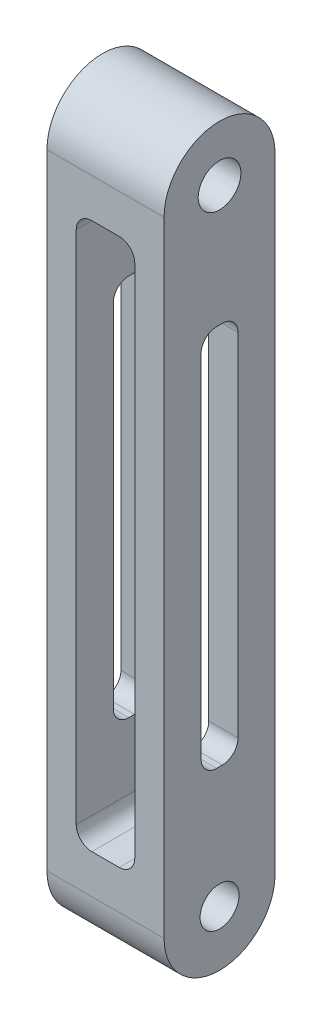
SolidWorks part; units mm, degrees
ref_plane "Front Plane" through (0, 0, 0) normal (0, 0, 1) x (1, 0, 0)
ref_plane "Top Plane" through (0, 0, 0) normal (0, 1, 0) x (1, 0, 0)
ref_plane "Right Plane" through (0, 0, 0) normal (1, 0, 0) x (0, 0, -1)
sketch "Sketch2" plane through (0, 0, 0) normal (1, 0, 0) x (0, 0, -1)
  line L0 (-7.1086, 0) -> (-7.1086, -80)
  line L1 (7.1086, 0) -> (7.1086, -80)
  line L2 (-7.1086, 0) -> (7.1086, 0)
  line L3 (7.1086, -80) -> (-7.1086, -80)
  line L4 (0, 0) -> (0, -40)
  line L6 (-0.3662, -15.5) -> (0.3662, -15.5)
  line L7 (-2.3662, -17.5) -> (-2.3662, -62.5)
  line L8 (-0.3662, -64.5) -> (0.3662, -64.5)
  line L9 (2.3662, -17.5) -> (2.3662, -62.5)
  line L10 (-2.3662, -15.5) -> (2.3662, -64.5) construction
  line L11 (-2.3662, -64.5) -> (2.3662, -15.5) construction
  circle A0 centre (0, 0) radius 2.7341
  circle A1 centre (0, 0) radius 7.1086
  circle A2 centre (0, -80) radius 7.1086
  circle A3 centre (0, -80) radius 2.5
  arc A4 (0.3662, -64.5) -> (2.3662, -62.5) centre (0.3662, -62.5) ccw
  arc A5 (-0.3662, -64.5) -> (-2.3662, -62.5) centre (-0.3662, -62.5) cw
  arc A6 (0.3662, -15.5) -> (2.3662, -17.5) centre (0.3662, -17.5) cw
  arc A7 (-2.3662, -17.5) -> (-0.3662, -15.5) centre (-0.3662, -17.5) cw
  dimension "D1" = 80
  dimension "D2" = 40
  dimension "D3" = 2
  dimension "D4" = 45
extrude "Boss-Extrude1" add sketch "Sketch2" along normal blind 15
sketch "Sketch3" plane through (0, 0, -7.1086) normal (0, 0, -1) x (-1, 0, 0)
  line L0 (-7.5, 0) -> (-7.5, -80)
  line L1 (-15, 0) -> (0, 0) construction
  line L2 (-15, -80) -> (0, -80) construction
  line L4 (-9.25, -5) -> (-5.75, -5)
  line L5 (-11.25, -7) -> (-11.25, -73)
  line L6 (-9.25, -75) -> (-5.75, -75)
  line L7 (-3.75, -7) -> (-3.75, -73)
  line L8 (-11.25, -5) -> (-3.75, -75) construction
  line L9 (-11.25, -75) -> (-3.75, -5) construction
  arc A0 (-11.25, -73) -> (-9.25, -75) centre (-9.25, -73) ccw
  arc A1 (-3.75, -73) -> (-5.75, -75) centre (-5.75, -73) cw
  arc A2 (-3.75, -7) -> (-5.75, -5) centre (-5.75, -7) ccw
  arc A3 (-11.25, -7) -> (-9.25, -5) centre (-9.25, -7) cw
  point P6 (-7.5, -40)
  dimension "D3" = 2
  dimension "D1" = 70
  dimension "D2" = 7.5
extrude "Cut-Extrude1" cut sketch "Sketch3" against normal blind 30 contours L7 A2 L4 L0 L6 A1 | A3 L5 A0 L6 L0 L4
